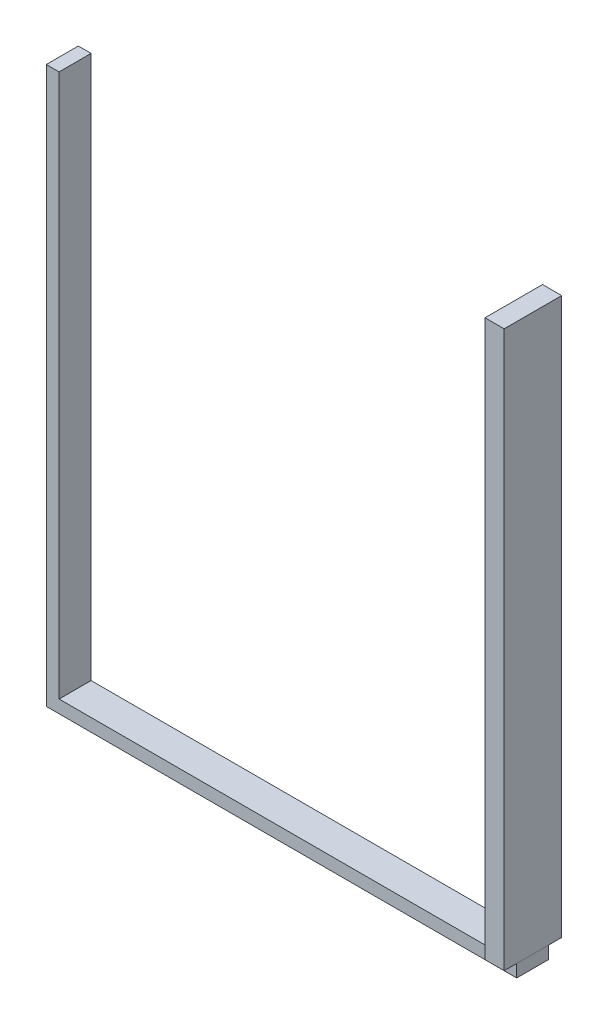
SolidWorks part; units mm, degrees
ref_plane "Front Plane" through (0, 0, 0) normal (0, 0, 1) x (1, 0, 0)
ref_plane "Top Plane" through (0, 0, 0) normal (0, 1, 0) x (1, 0, 0)
ref_plane "Right Plane" through (0, 0, 0) normal (1, 0, 0) x (0, 0, -1)
sketch "Sketch1" plane through (0, 0, 0) normal (0, 1, 0) x (1, 0, 0)
  line L1 (0, 0) -> (4.0005, 0)
  line L2 (0, 0) -> (0, 10)
  line L3 (0, 10) -> (4.0005, 10)
  line L4 (4.0005, 0) -> (4.0005, 10)
extrude "Boss-Extrude1" add sketch "Sketch1" along normal blind 173.736
sketch "Sketch2" plane through (4.0005, 0, 0) normal (1, 0, 0) x (0, 0, -1)
  line L0 (10, 173.736) -> (10, 0) construction
  line L1 (0, 0) -> (10, 0)
  line L2 (0, 0) -> (0, 4)
  line L3 (0, 4) -> (10, 4)
  line L4 (10, 0) -> (10, 4)
extrude "Boss-Extrude2" add sketch "Sketch2" along normal blind 143
sketch "Sketch4" plane through (0, 4, 0) normal (0, 1, 0) x (1, 0, 0)
  line L1 (147.0771, -3.9912) -> (141.0972, -3.9912)
  line L2 (147.0771, -3.9912) -> (147.0771, 13.9875)
  line L3 (147.0771, 13.9875) -> (141.0972, 13.9875)
  line L4 (141.0972, -3.9912) -> (141.0972, 13.9875)
extrude "Boss-Extrude3" add sketch "Sketch4" along normal blind 173.736
